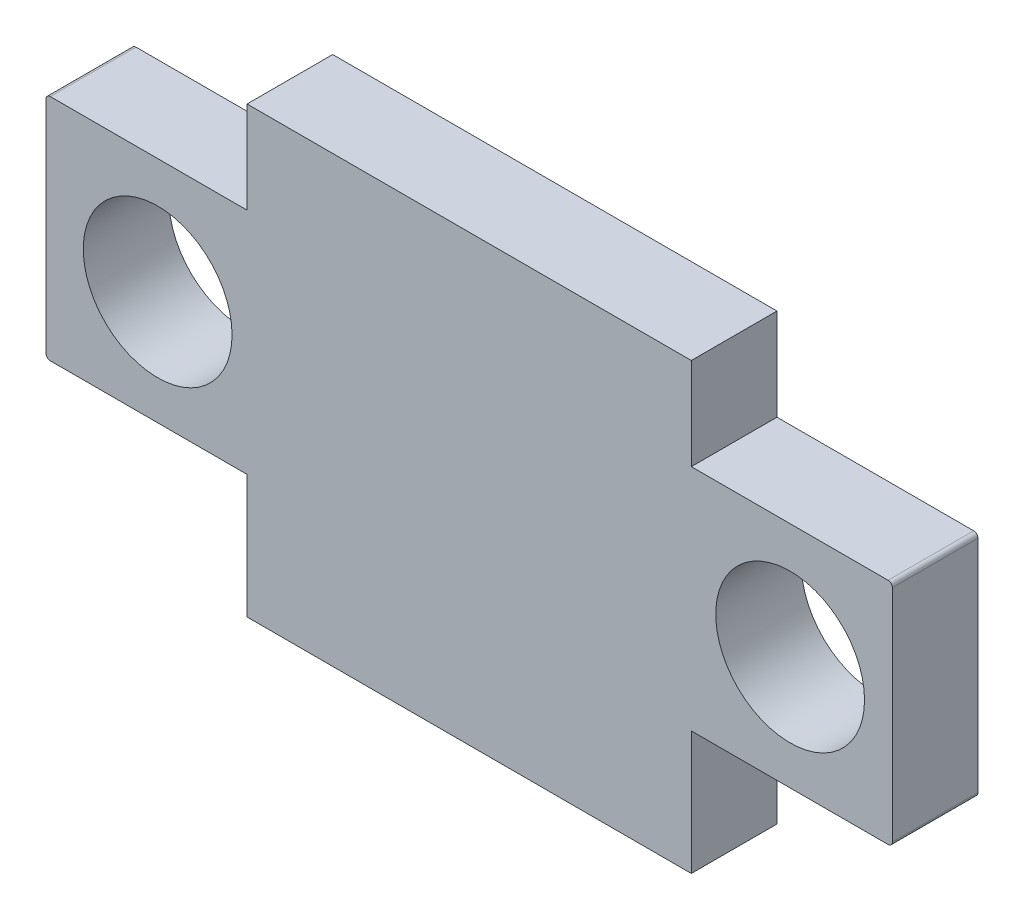
SolidWorks part; units mm, degrees
ref_plane "Front Plane" through (0, 0, 0) normal (0, 0, 1) x (1, 0, 0)
ref_plane "Top Plane" through (0, 0, 0) normal (0, 1, 0) x (1, 0, 0)
ref_plane "Right Plane" through (0, 0, 0) normal (1, 0, 0) x (0, 0, -1)
sketch "Sketch1" plane through (0, 0, 0) normal (0, 0, 1) x (1, 0, 0)
  line L1 (-10.375, 6.0805) -> (-19.5642, 6.0805)
  line L2 (-10.375, 6.0805) -> (-10.375, -4.6084)
  line L3 (-10.375, -4.6084) -> (-19.5642, -4.6084)
  line L4 (-19.7642, 5.8805) -> (-19.7642, -4.4084)
  line L6 (10.375, 6.0805) -> (19.5642, 6.0805)
  line L7 (10.375, 6.0805) -> (10.375, -4.6084)
  line L8 (10.375, -4.6084) -> (19.5642, -4.6084)
  line L9 (19.7642, 5.8805) -> (19.7642, -4.4084)
  line L11 (-10.375, -10.375) -> (10.375, -10.375)
  line L12 (-10.375, -10.375) -> (-10.375, 10.375)
  line L13 (-10.375, 10.375) -> (10.375, 10.375)
  line L14 (10.375, -10.375) -> (10.375, 10.375)
  line L15 (-10.375, -10.375) -> (10.375, 10.375) construction
  line L16 (-10.375, 10.375) -> (10.375, -10.375) construction
  circle A0 centre (-14.5492, 0.6881) radius 3.475
  circle A1 centre (14.9894, 0.6881) radius 3.475
  arc A2 (-19.7642, -4.4084) -> (-19.5642, -4.6084) centre (-19.5642, -4.4084) ccw
  arc A3 (19.5642, -4.6084) -> (19.7642, -4.4084) centre (19.5642, -4.4084) ccw
  arc A4 (19.7642, 5.8805) -> (19.5642, 6.0805) centre (19.5642, 5.8805) ccw
  arc A5 (-19.5642, 6.0805) -> (-19.7642, 5.8805) centre (-19.5642, 5.8805) ccw
  point P4 (0, 0)
  dimension "D1" = 0.2
  dimension "D2" = 29.5387
  dimension "D3" = 5.3925
  dimension "D4" = 5.3925
  dimension "D5" = 20.75
extrude "Boss-Extrude1" add sketch "Sketch1" along normal blind 4 contours L1 A5 L4 A2 L3 L2 A0 | L11 L14 L7 L13 L12 L2 | L9 A4 L6 L7 L8 A3 A1
